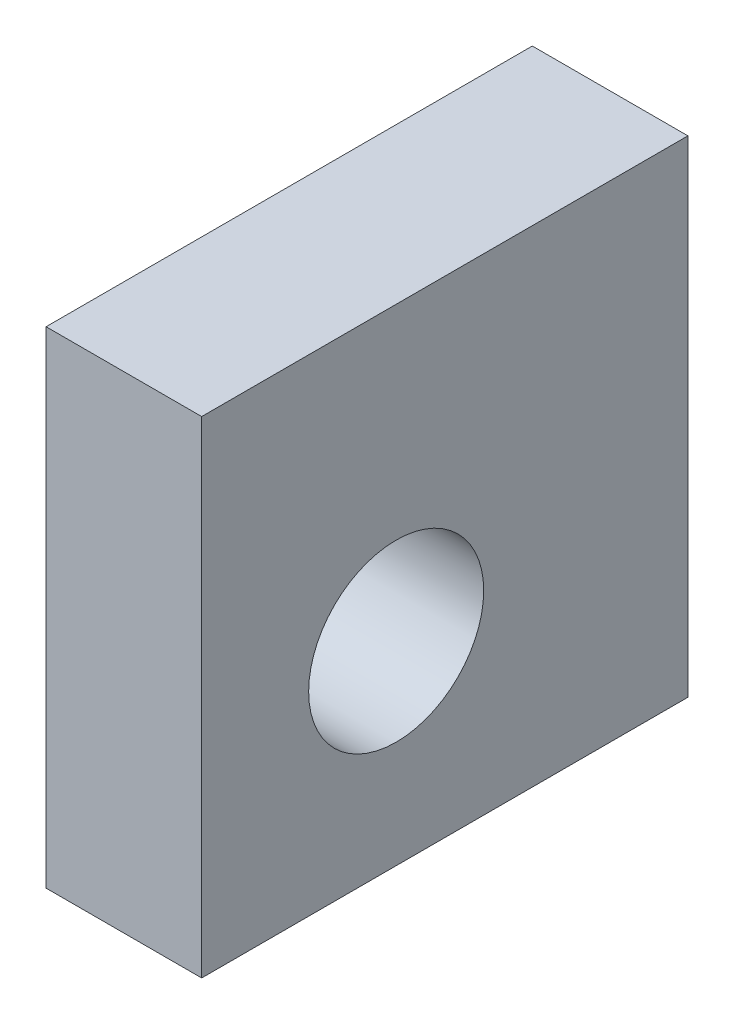
SolidWorks part; units mm, degrees
ref_plane "Front Plane" through (0, 0, 0) normal (0, 0, 1) x (1, 0, 0)
ref_plane "Top Plane" through (0, 0, 0) normal (0, 1, 0) x (1, 0, 0)
ref_plane "Right Plane" through (0, 0, 0) normal (1, 0, 0) x (0, 0, -1)
sketch "Sketch1" plane through (0, 0, 0) normal (1, 0, 0) x (0, 0, -1)
  line L1 (-12.5, -12.5) -> (12.5, -12.5)
  line L2 (-12.5, -12.5) -> (-12.5, 12.5)
  line L3 (-12.5, 12.5) -> (12.5, 12.5)
  line L4 (12.5, -12.5) -> (12.5, 12.5)
  line L5 (-12.5, -12.5) -> (12.5, 12.5) construction
  line L6 (-12.5, 12.5) -> (12.5, -12.5) construction
  circle A1 centre (-2.5, -2.5) radius 4.5
  point P0 (0, 0)
  point P8 (0, 0)
  point P9 (0, 0)
  dimension "D3" = 15
  dimension "D4" = 9
  dimension "D1" = 25
  dimension "D2" = 25
  dimension "D5" = 15
extrude "Boss-Extrude1" add sketch "Sketch1" along normal blind 8
